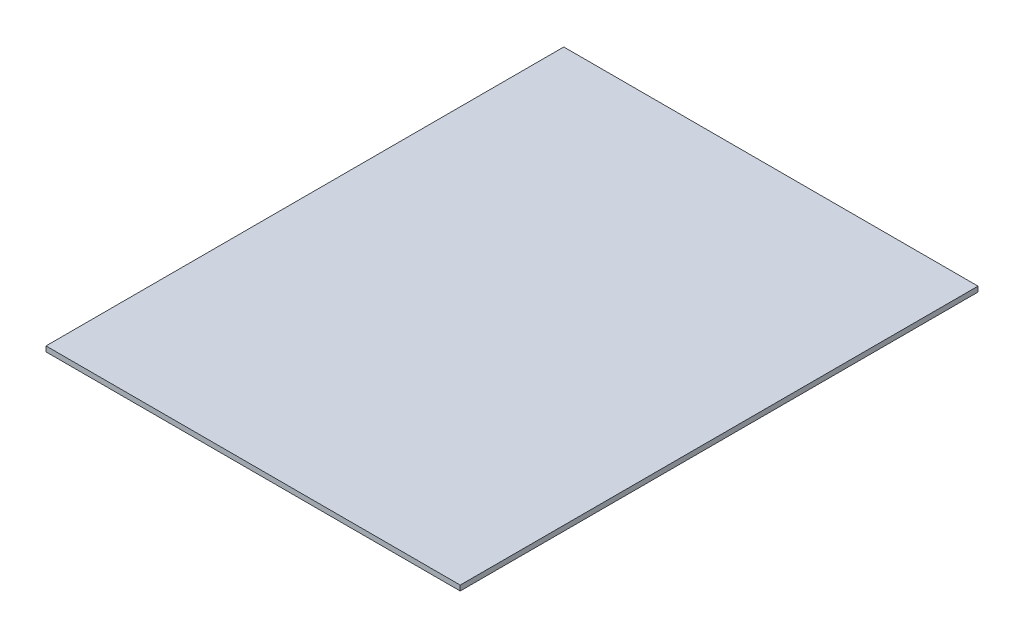
SolidWorks part; units mm, degrees
ref_plane "Front Plane" through (0, 0, 0) normal (0, 0, 1) x (1, 0, 0)
ref_plane "Top Plane" through (0, 0, 0) normal (0, 1, 0) x (1, 0, 0)
ref_plane "Right Plane" through (0, 0, 0) normal (1, 0, 0) x (0, 0, -1)
sketch "Sketch2" plane through (0, 0, 0) normal (0, 1, 0) x (1, 0, 0)
  line L1 (-200, 250) -> (200, 250)
  line L2 (-200, 250) -> (-200, -250)
  line L3 (-200, -250) -> (200, -250)
  line L4 (200, 250) -> (200, -250)
  line L5 (-200, 250) -> (200, -250) construction
  line L6 (-200, -250) -> (200, 250) construction
  point P0 (0, 0)
  dimension "D1" = 500
  dimension "D2" = 400
extrude "Boss-Extrude1" add sketch "Sketch2" along normal blind 5
